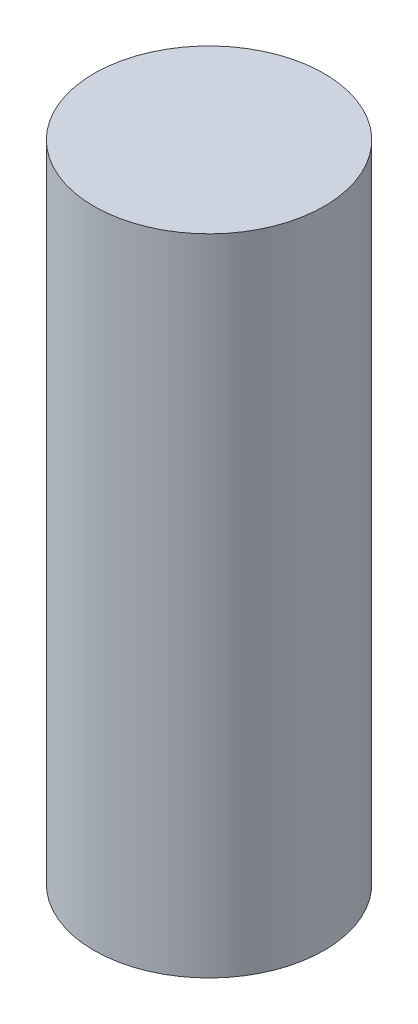
SolidWorks part; units mm, degrees
ref_plane "Спереди" through (0, 0, 0) normal (0, 0, 1) x (1, 0, 0)
ref_plane "Сверху" through (0, 0, 0) normal (0, 1, 0) x (1, 0, 0)
ref_plane "Справа" through (0, 0, 0) normal (1, 0, 0) x (0, 0, -1)
other "Configuration Table"
sketch "Sketch2" plane through (0, 0, 0) normal (0, 1, 0) x (1, 0, 0)
  line L0 (0, -23.1726) -> (0, 23.1726) construction
  line L1 (42.2452, 0) -> (-42.2452, 0) construction
  circle A0 centre (0, 0) radius 12.5
  point P4 (0, 0)
  point P8 (0, 0)
  dimension "D1" = 25
extrude "Boss-Extrude1" add sketch "Sketch2" against normal blind 70
